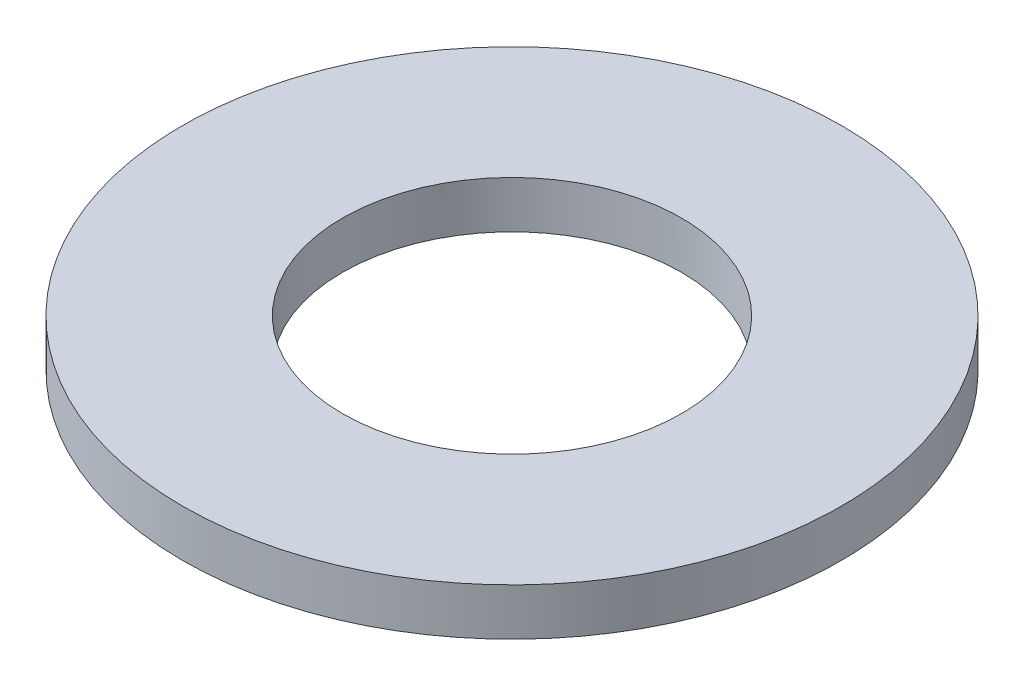
SolidWorks part; units mm, degrees
ref_plane "Front Plane" through (0, 0, 0) normal (0, 0, 1) x (1, 0, 0)
ref_plane "Top Plane" through (0, 0, 0) normal (0, 1, 0) x (1, 0, 0)
ref_plane "Right Plane" through (0, 0, 0) normal (1, 0, 0) x (0, 0, -1)
sketch "Sketch1" plane through (0, 0, 0) normal (0, 1, 0) x (1, 0, 0)
  circle A0 centre (0, 0) radius 1750
extrude "Boss-Extrude1" add sketch "Sketch1" along normal blind 500
sketch "Sketch2" plane through (0, 500, 0) normal (0, 1, 0) x (1, 0, 0)
  circle A0 centre (0, 0) radius 900
extrude "Cut-Extrude2" cut sketch "Sketch2" against normal blind 300
sketch "Sketch3" plane through (0, 0, 0) normal (0, -1, 0) x (1, 0, 0)
  circle A0 centre (0, 0) radius 600
extrude "Cut-Extrude3" cut sketch "Sketch3" against normal blind 300
sketch "Sketch4" plane through (0, 0, 0) normal (0, -1, 0) x (-1, 0, 0)
  circle A0 centre (0, 0) radius 950
  circle A1 centre (0, 0) radius 1700
extrude "Cut-Extrude5" cut sketch "Sketch4" against normal blind 490
sketch "Sketch5" plane through (0, 0, 0) normal (0, 0, 1) x (1, 0, 0)
  line L0 (0, 0) -> (0, 250)
  line L1 (0, 250) -> (1750, 250)
  line L2 (1750, 0) -> (1750, 500) construction
  line L3 (1750, 250) -> (1750, 0)
  line L4 (1750, 0) -> (-1750, 0)
  line L5 (-1750, 0) -> (-1750, 250)
  line L6 (-1750, 500) -> (-1750, 0) construction
  line L7 (-1750, 250) -> (0, 250)
extrude "Cut-Extrude6" cut sketch "Sketch5" against normal through all both and the other way through all contours L7 L5 L4 L0 | L4 L3 L1 L0
